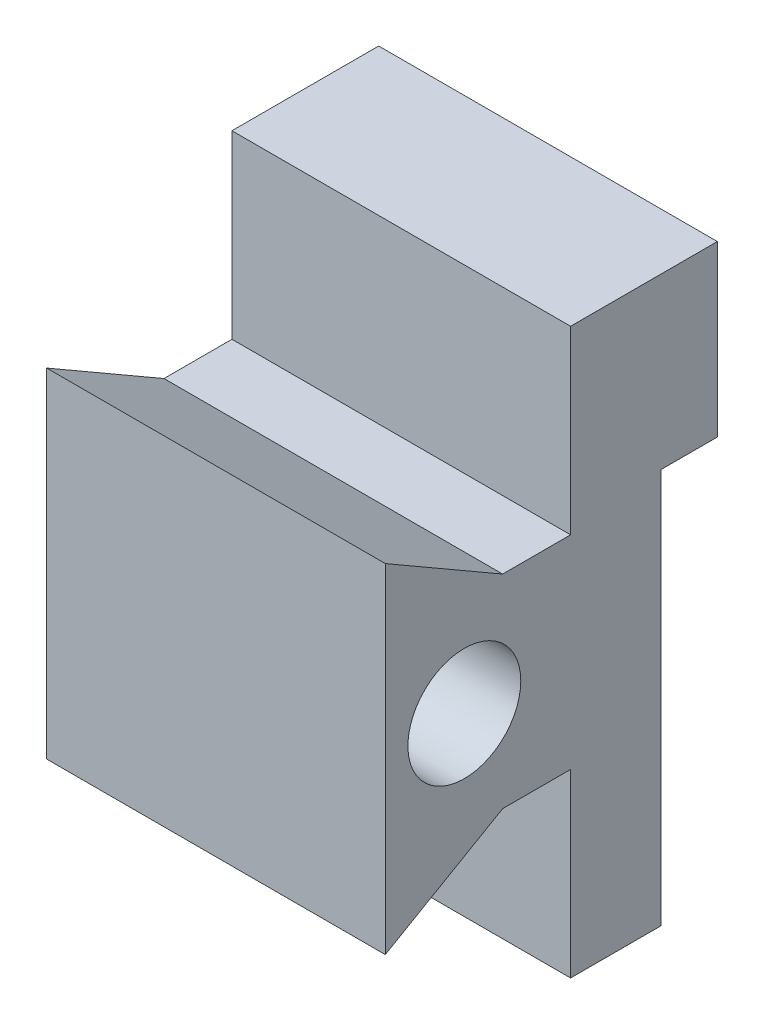
SolidWorks part; units mm, degrees
material "Polyetheretherketone (PEEK)"
ref_plane "Front Plane" through (0, 0, 0) normal (0, 0, 1) x (1, 0, 0)
ref_plane "Top Plane" through (0, 0, 0) normal (0, 1, 0) x (1, 0, 0)
ref_plane "Right Plane" through (0, 0, 0) normal (1, 0, 0) x (0, 0, -1)
sketch "Sketch1" plane through (0, 0, 0) normal (1, 0, 0) x (0, 0, -1)
  line L0 (0, -1.5) -> (0, 1.5)
  line L1 (0, 1.5) -> (1.0392, 0.9)
  line L2 (1.0392, -0.9) -> (1.6413, -0.9)
  line L3 (1.6413, 2.5) -> (2.4413, 2.5)
  line L4 (2.4413, 2.5) -> (2.4413, -2.5)
  line L5 (2.4413, -2.5) -> (1.6413, -2.5)
  line L6 (1.6413, -0.9) -> (1.6413, -2.5)
  line L7 (1.0392, -0.9) -> (0, -1.5)
  line L8 (1.0392, 0.9) -> (1.6413, 0.9)
  line L9 (1.6413, 0.9) -> (1.6413, 2.5)
  point P4 (0, 0)
  point P12 (2.4413, 0)
  dimension "D1" = 3
  dimension "D2" = 60
  dimension "D3" = 60
  dimension "D4" = 5
  dimension "D5" = 0.8
  dimension "D6" = 0.6021
  dimension "D7" = 1.8
extrude "Boss-Extrude1" add sketch "Sketch1" along normal blind 3
sketch "Sketch2" plane through (3, 0, 0) normal (1, 0, 0) x (0, 0, -1)
  circle A0 centre (0.7, 0) radius 0.5
  dimension "D1" = 1
  dimension "D2" = 0.7
extrude "Cut-Extrude1" cut sketch "Sketch2" against normal through all
sketch "Sketch3" plane through (0, 0, -2.4413) normal (0, 0, -1) x (-1, 0, 0)
  line L1 (-3, 2.5) -> (0, 2.5)
  line L2 (-3, 2.5) -> (-3, 1)
  line L3 (-3, 1) -> (0, 1)
  line L4 (0, 2.5) -> (0, 1)
  point P4 (0, 0)
  point P6 (0, 0)
extrude "Boss-Extrude2" add sketch "Sketch3" along normal blind 0.5
